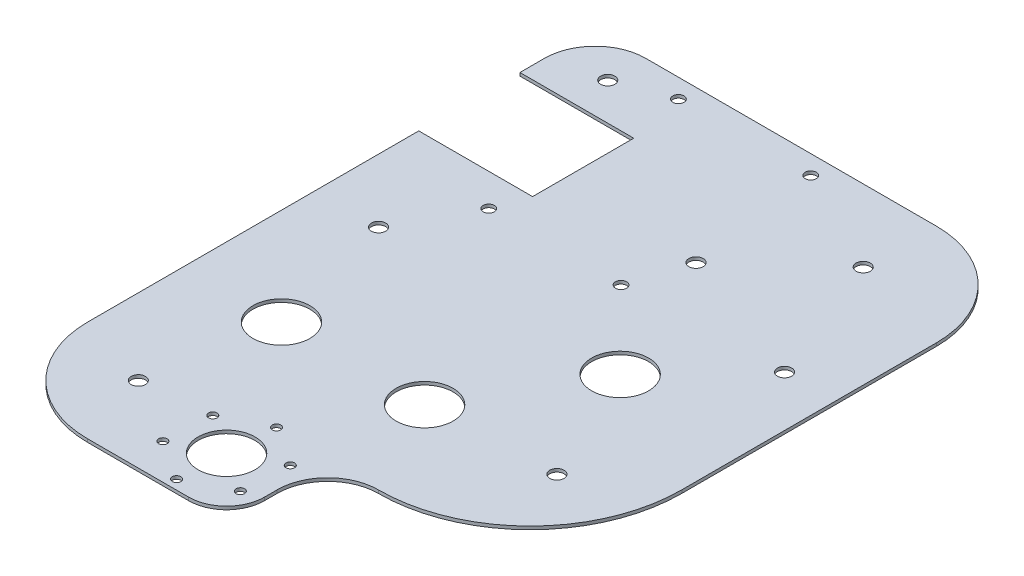
SolidWorks part; units mm, degrees
ref_plane "Front Plane" through (0, 0, 0) normal (0, 0, 1) x (1, 0, 0)
ref_plane "Top Plane" through (0, 0, 0) normal (0, 1, 0) x (1, 0, 0)
ref_plane "Right Plane" through (0, 0, 0) normal (1, 0, 0) x (0, 0, -1)
sketch "Sketch1" plane through (0, 0, 0) normal (0, 1, 0) x (1, 0, 0)
  line L0 (9.4615, 127.3918) -> (111.0615, 25.7918) construction
  line L1 (-111.0615, -127.3918) -> (111.0615, -127.3918)
  line L2 (-111.0615, -127.3918) -> (-111.0615, 127.3918)
  line L3 (-111.0615, 127.3918) -> (111.0615, 127.3918)
  line L4 (111.0615, -127.3918) -> (111.0615, 127.3918)
  line L5 (-111.0615, -127.3918) -> (111.0615, 127.3918) construction
  line L6 (-111.0615, 127.3918) -> (111.0615, -127.3918) construction
  line L7 (111.0615, 127.3918) -> (9.4615, 127.3918) construction
  line L8 (111.0615, 127.3918) -> (111.0615, 25.7918) construction
  line L9 (111.0615, 25.7918) -> (9.4615, 25.7918) construction
  line L10 (9.4615, 127.3918) -> (9.4615, 25.7918) construction
  line L11 (111.0615, 127.3918) -> (9.4615, 25.7918) construction
  line L12 (9.4615, 25.7918) -> (9.4615, -16.4992) construction
  line L13 (-62.4205, -78.7508) -> (9.4615, -78.7508) construction
  line L14 (-8.499, -96.7113) -> (27.422, -60.7903) construction
  circle A0 centre (45.4025, -16.4992) radius 35.941 construction
  circle A1 centre (9.4615, -78.7508) radius 35.941 construction
  circle A2 centre (-62.4205, -78.7508) radius 35.941 construction
  circle A3 centre (9.4615, -78.7508) radius 14.2875
  circle A4 centre (45.4025, -16.4992) radius 14.2875
  circle A5 centre (-62.4205, -78.7508) radius 14.2875
  point P0 (0, 0)
  point P9 (60.2615, 76.5918)
  point P13 (45.4025, 19.4418)
  point P18 (-98.3615, -78.7508)
  point P19 (-62.4205, -114.6918)
  point P25 (9.4615, -78.7508)
  dimension "D3" = 71.882
  dimension "D5" = 12.7
  dimension "D7" = 28.575
  dimension "D1" = 101.6
  dimension "D2" = 101.6
  dimension "D4" = 6.35
  dimension "D6" = 12.7
  dimension "D8" = 50.8
  dimension "D10" = 45
extrude "Boss-Extrude1" add sketch "Sketch1" along normal blind 1.5875
sketch "Sketch4" plane through (0, 0, 0) normal (0, -1, 0) x (-1, 0, 0)
  circle A0 centre (59.6925, 117.8668) radius 2.8067
  circle A1 centre (59.6925, 22.6168) radius 2.8067
  circle A2 centre (-6.7335, 117.8668) radius 2.8067
  circle A3 centre (-6.7335, 22.6168) radius 2.8067
  dimension "D1" = 5.6134
extrude "Cut-Extrude1" cut sketch "Sketch4" against normal through all
sketch "Sketch5" plane through (0, 0, 0) normal (0, -1, 0) x (1, 0, 0)
  circle A0 centre (59.7701, -91.1952) radius 1.5875
  dimension "D1" = 3.175
extrude "Cut-Extrude2" cut sketch "Sketch5" against normal through all
sketch "Sketch6" plane through (0, 0, 127.3918) normal (0, 0, 1) x (1, 0, 0)
  line L1 (-111.0615, 0) -> (111.0615, 0)
  line L2 (-111.0615, 0) -> (-111.0615, 1.5875)
  line L3 (-111.0615, 1.5875) -> (111.0615, 1.5875)
  line L4 (111.0615, 0) -> (111.0615, 1.5875)
extrude "Boss-Extrude2" add sketch "Sketch6" along normal blind 50.8
sketch "Sketch7" plane through (0, 0, 0) normal (0, -1, 0) x (-1, 0, 0)
  line L1 (-111.0615, -178.1918) -> (-9.4615, -178.1918)
  line L2 (-111.0615, -178.1918) -> (-111.0615, -127.3918)
  line L3 (-111.0615, -127.3918) -> (-9.4615, -127.3918)
  line L4 (-9.4615, -178.1918) -> (-9.4615, -127.3918)
  dimension "D1" = 101.6
  dimension "D2" = 50.8
extrude "Cut-Extrude3" cut sketch "Sketch7" against normal through all
sketch "Sketch8" plane through (0, 1.5875, 0) normal (0, 1, 0) x (1, 0, 0)
  line L0 (9.4615, -178.1918) -> (9.4615, -127.3918) construction
  line L1 (9.4615, -178.1918) -> (-111.0615, -178.1918) construction
  circle A0 centre (-19.1135, -149.6168) radius 14.2875
  dimension "D1" = 28.575
  dimension "D3" = 28.575
  dimension "D2" = 28.575
extrude "Cut-Extrude5" cut sketch "Sketch8" against normal through all
sketch "Sketch9" plane through (0, 1.5875, 0) normal (0, 1, 0) x (1, 0, 0)
  circle A0 centre (-17.8018, -125.8405) radius 2.15
  circle A1 centre (2.1333, -138.8646) radius 2.15
  circle A2 centre (0.8216, -162.6409) radius 2.15
  circle A3 centre (-20.4252, -173.3932) radius 2.15
  circle A4 centre (-40.3603, -160.3691) radius 2.15
  circle A5 centre (-39.0486, -136.5927) radius 2.15
  dimension "D1" = 4.3
extrude "Cut-Extrude6" cut sketch "Sketch9" against normal through all
sketch "Sketch10" plane through (0, 1.5875, 0) normal (0, 1, 0) x (1, 0, 0)
  line L0 (-111.0615, 127.3918) -> (-111.0615, -178.1918) construction
  line L1 (-111.0615, 38.8427) -> (-53.9115, 38.8427)
  line L2 (-111.0615, 38.8427) -> (-111.0615, 89.6427)
  line L3 (-111.0615, 89.6427) -> (-53.9115, 89.6427)
  line L4 (-53.9115, 38.8427) -> (-53.9115, 89.6427)
  line L5 (-111.0615, 64.2427) -> (-53.9115, 64.2427) construction
  dimension "D1" = 50.8
  dimension "D2" = 57.15
extrude "Cut-Extrude7" cut sketch "Sketch10" against normal through all
sketch "Sketch11" plane through (0, 1.5875, 0) normal (0, 1, 0) x (1, 0, 0)
  line L0 (9.4615, -178.1918) -> (-111.0615, -178.1918) construction
  line L1 (9.4615, -178.1918) -> (9.4615, -127.3918) construction
  line L2 (-9.5885, -178.1918) -> (9.4615, -178.1918)
  line L3 (9.4615, -178.1918) -> (9.4615, -159.1418)
  arc A0 (-9.5885, -178.1918) -> (9.4615, -159.1418) centre (-9.5885, -159.1418) ccw
  dimension "D1" = 38.1
extrude "Cut-Extrude8" cut sketch "Sketch11" against normal through all
fillet "Fillet2" radius 25.4 1 edges at (9.4615, 0.7937, 127.3918)
sketch "Sketch12" plane through (0, 1.5875, 0) normal (0, 1, 0) x (1, 0, 0)
  line L0 (111.0615, -127.3918) -> (111.0615, 127.3918) construction
  line L1 (34.8615, -127.3918) -> (111.0615, -127.3918) construction
  line L2 (111.0615, -51.1918) -> (111.0615, -127.3918)
  line L3 (111.0615, -127.3918) -> (34.8615, -127.3918)
  arc A0 (34.8615, -127.3918) -> (111.0615, -51.1918) centre (34.8615, -51.1918) ccw
  dimension "D1" = 152.4
extrude "Cut-Extrude9" cut sketch "Sketch12" against normal through all
sketch "Sketch13" plane through (0, 1.5875, 0) normal (0, 1, 0) x (1, 0, 0)
  line L0 (111.0615, 127.3918) -> (-111.0615, 127.3918) construction
  line L1 (111.0615, -51.1918) -> (111.0615, 127.3918) construction
  line L2 (60.2615, 127.3918) -> (111.0615, 127.3918)
  line L3 (111.0615, 127.3918) -> (111.0615, 76.5918)
  arc A0 (111.0615, 76.5918) -> (60.2615, 127.3918) centre (60.2615, 76.5918) ccw
  dimension "D1" = 101.6
extrude "Cut-Extrude10" cut sketch "Sketch13" against normal through all
sketch "Sketch14" plane through (0, 1.5875, 0) normal (0, 1, 0) x (1, 0, 0)
  line L0 (-111.0615, 127.3918) -> (-111.0615, 89.6427) construction
  line L1 (60.2615, 127.3918) -> (-111.0615, 127.3918) construction
  line L2 (-85.6615, 127.3918) -> (-111.0615, 127.3918)
  line L3 (-111.0615, 127.3918) -> (-111.0615, 101.9918)
  arc A0 (-85.6615, 127.3918) -> (-111.0615, 101.9918) centre (-85.6615, 101.9918) ccw
  dimension "D1" = 50.8
extrude "Cut-Extrude11" cut sketch "Sketch14" against normal through all
sketch "Sketch15" plane through (0, 1.5875, 0) normal (0, 1, 0) x (1, 0, 0)
  line L0 (-111.0615, 38.8427) -> (-111.0615, -178.1918) construction
  line L1 (-9.5885, -178.1918) -> (-111.0615, -178.1918) construction
  line L2 (-111.0615, -127.3918) -> (-111.0615, -178.1918)
  line L3 (-111.0615, -178.1918) -> (-60.2615, -178.1918)
  arc A0 (-111.0615, -127.3918) -> (-60.2615, -178.1918) centre (-60.2615, -127.3918) ccw
  dimension "D1" = 101.6
extrude "Cut-Extrude12" cut sketch "Sketch15" against normal through all
sketch "Sketch16" plane through (0, 0, 0) normal (0, -1, 0) x (1, 0, 0)
  line L0 (-111.0615, -38.8427) -> (-111.0615, 127.3918) construction
  line L1 (-60.2615, 178.1918) -> (-9.5885, 178.1918) construction
  line L2 (60.2615, -127.3918) -> (-85.6615, -127.3918) construction
  line L3 (111.0615, 51.1918) -> (111.0615, -76.5918) construction
  line L5 (-111.0615, -101.9918) -> (-111.0615, -89.6427) construction
  circle A0 centre (-85.6615, -108.3418) radius 1.27
  circle A1 centre (-79.3115, 13.0918) radius 1.27
  circle A2 centre (-72.9615, 140.0918) radius 1.27
  circle A3 centre (72.9615, 75.8082) radius 1.27
  circle A4 centre (85.6615, -25.7918) radius 1.27
  circle A5 centre (15.8115, -51.1918) radius 1.27
  point P0 (-72.9615, 140.0918)
  point P1 (-79.3115, 13.0918)
  point P2 (72.9615, 75.8082)
  point P3 (85.6615, -25.7918)
  point P4 (15.8115, -51.1918)
  point P14 (-85.6615, -108.3418)
  dimension "D13" = 2.54
  dimension "D1" = 31.75
  dimension "D2" = 165.1
  dimension "D3" = 38.1
  dimension "D4" = 38.1
  dimension "D5" = 38.1
  dimension "D6" = 203.2
  dimension "D7" = 25.4
  dimension "D8" = 101.6
  dimension "D9" = 76.2
  dimension "D10" = 95.25
  dimension "D11" = 25.4
  dimension "D12" = 19.05
extrude "Cut-Extrude13" cut sketch "Sketch16" against normal through all
hole_wizard "1/4 Clearance Hole1" positions "Sketch20" profile "Sketch19" hole size "1/4" standard "ANSI Inch" end condition through all
sketch "Sketch20" plane through (0, 1.5875, 0) normal (0, 1, 0) x (1, 0, 0)
  point P0 (-85.6615, 108.3418)
  point P3 (-79.3115, -13.0918)
  point P6 (-72.9615, -140.0918)
  point P9 (72.9615, -75.8082)
  point P12 (85.6615, 25.7918)
  point P15 (59.7701, 91.1952)
  point P18 (15.8115, 51.1918)
sketch "Sketch19" plane through (-85.6615, 1.5875, -108.3418) normal (1, 0, 0) x (0, 0, 1)
  line L0 (0, 0) -> (0, 1.5875)
  line L1 (0, 1.5875) -> (3.5712, 1.5875)
  line L2 (3.5712, 1.5875) -> (3.5712, 0)
  line L5 (3.5712, 0) -> (0, 0)
  line L11 (0, -6.35) -> (0, 107.95) construction
  dimension "Thru Hole Dia." = 7.1425
  dimension "Thru Hole Depth" = 1.5875
